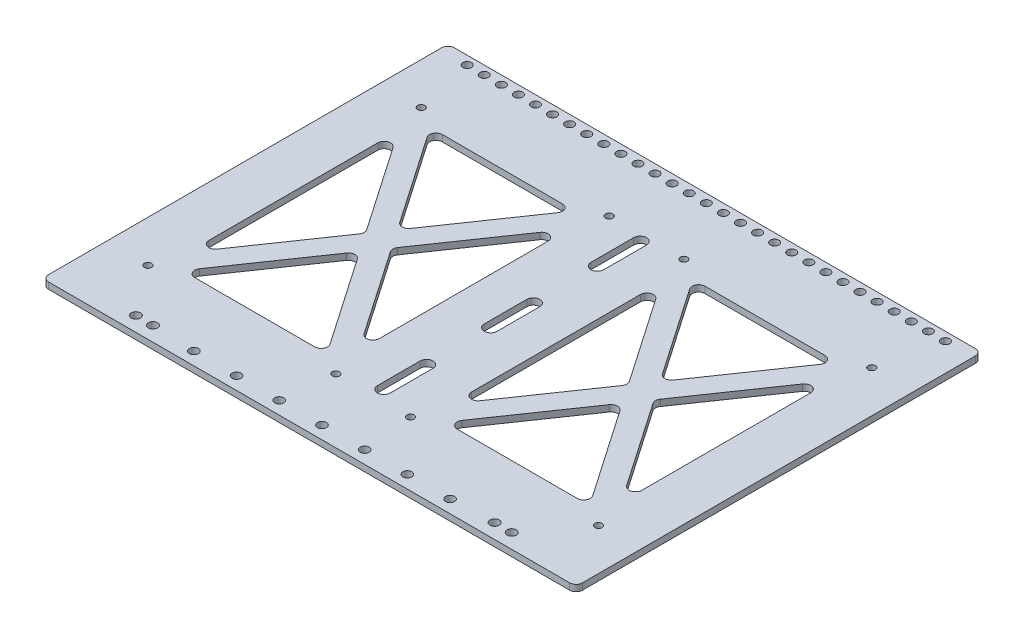
SolidWorks part; units mm, degrees
material "Thornel Mat VMA"
ref_plane "前视基准面" through (0, 0, 0) normal (0, 0, 1) x (1, 0, 0)
ref_plane "上视基准面" through (0, 0, 0) normal (0, 1, 0) x (1, 0, 0)
ref_plane "右视基准面" through (0, 0, 0) normal (1, 0, 0) x (0, 0, -1)
other "Configuration Table"
sketch "草图1" plane through (0, 0, 0) normal (0, 1, 0) x (1, 0, 0)
  line L1 (-125, -95) -> (125, -95)
  line L2 (-125, -95) -> (-125, 95)
  line L3 (-125, 95) -> (125, 95)
  line L4 (125, -95) -> (125, 95)
  line L5 (-125, -95) -> (125, 95) construction
  line L6 (-125, 95) -> (125, -95) construction
  point P0 (0, 0)
  dimension "D1" = 250
  dimension "D2" = 190
extrude "凸台-拉伸1" add sketch "草图1" along normal blind 3 contours L2 L1 L4 L3
sketch "草图2" plane through (0, 0, 0) normal (0, -1, 0) x (1, 0, 0)
  arc A4 (56, -93) -> (56, -89) centre (56, -91) ccw
  arc A5 (56, -89) -> (56, -93) centre (56, -91) ccw
  arc A8 (-112, -93) -> (-112, -89) centre (-112, -91) ccw
  arc A9 (-112, -89) -> (-112, -93) centre (-112, -91) ccw
  arc A12 (-104, -93) -> (-104, -89) centre (-104, -91) ccw
  arc A13 (-104, -89) -> (-104, -93) centre (-104, -91) ccw
  arc A16 (-96, -93) -> (-96, -89) centre (-96, -91) ccw
  arc A17 (-96, -89) -> (-96, -93) centre (-96, -91) ccw
  arc A20 (-88, -93) -> (-88, -89) centre (-88, -91) ccw
  arc A21 (-88, -89) -> (-88, -93) centre (-88, -91) ccw
  arc A24 (-48, -93) -> (-48, -89) centre (-48, -91) ccw
  arc A25 (-48, -89) -> (-48, -93) centre (-48, -91) ccw
  arc A28 (-80, -93) -> (-80, -89) centre (-80, -91) ccw
  arc A29 (-80, -89) -> (-80, -93) centre (-80, -91) ccw
  arc A32 (-72, -93) -> (-72, -89) centre (-72, -91) ccw
  arc A33 (-72, -89) -> (-72, -93) centre (-72, -91) ccw
  arc A36 (-64, -93) -> (-64, -89) centre (-64, -91) ccw
  arc A37 (-64, -89) -> (-64, -93) centre (-64, -91) ccw
  arc A40 (-56, -93) -> (-56, -89) centre (-56, -91) ccw
  arc A41 (-56, -89) -> (-56, -93) centre (-56, -91) ccw
  arc A44 (64, -93) -> (64, -89) centre (64, -91) ccw
  arc A45 (64, -89) -> (64, -93) centre (64, -91) ccw
  arc A48 (72, -93) -> (72, -89) centre (72, -91) ccw
  arc A49 (72, -89) -> (72, -93) centre (72, -91) ccw
  arc A52 (80, -93) -> (80, -89) centre (80, -91) ccw
  arc A53 (80, -89) -> (80, -93) centre (80, -91) ccw
  arc A56 (88, -93) -> (88, -89) centre (88, -91) ccw
  arc A57 (88, -89) -> (88, -93) centre (88, -91) ccw
  arc A60 (96, -93) -> (96, -89) centre (96, -91) ccw
  arc A61 (96, -89) -> (96, -93) centre (96, -91) ccw
  arc A64 (104, -93) -> (104, -89) centre (104, -91) ccw
  arc A65 (104, -89) -> (104, -93) centre (104, -91) ccw
  arc A68 (112, -93) -> (112, -89) centre (112, -91) ccw
  arc A69 (112, -89) -> (112, -93) centre (112, -91) ccw
  arc A72 (32, -93) -> (32, -89) centre (32, -91) ccw
  arc A73 (32, -89) -> (32, -93) centre (32, -91) ccw
  arc A76 (24, -93) -> (24, -89) centre (24, -91) ccw
  arc A77 (24, -89) -> (24, -93) centre (24, -91) ccw
  arc A80 (16, -93) -> (16, -89) centre (16, -91) ccw
  arc A81 (16, -89) -> (16, -93) centre (16, -91) ccw
  arc A84 (8, -93) -> (8, -89) centre (8, -91) ccw
  arc A85 (8, -89) -> (8, -93) centre (8, -91) ccw
  arc A88 (0, -93) -> (0, -89) centre (0, -91) ccw
  arc A89 (0, -89) -> (0, -93) centre (0, -91) ccw
  arc A92 (-8, -93) -> (-8, -89) centre (-8, -91) ccw
  arc A93 (-8, -89) -> (-8, -93) centre (-8, -91) ccw
  arc A96 (-16, -93) -> (-16, -89) centre (-16, -91) ccw
  arc A97 (-16, -89) -> (-16, -93) centre (-16, -91) ccw
  arc A100 (-24, -93) -> (-24, -89) centre (-24, -91) ccw
  arc A101 (-24, -89) -> (-24, -93) centre (-24, -91) ccw
  arc A104 (-32, -93) -> (-32, -89) centre (-32, -91) ccw
  arc A105 (-32, -89) -> (-32, -93) centre (-32, -91) ccw
  arc A108 (-40, -93) -> (-40, -89) centre (-40, -91) ccw
  arc A109 (-40, -89) -> (-40, -93) centre (-40, -91) ccw
  arc A112 (40, -93) -> (40, -89) centre (40, -91) ccw
  arc A113 (40, -89) -> (40, -93) centre (40, -91) ccw
  arc A116 (48, -93) -> (48, -89) centre (48, -91) ccw
  arc A117 (48, -89) -> (48, -93) centre (48, -91) ccw
extrude "切除-拉伸1" cut sketch "草图2" against normal through all both
sketch "草图3" plane through (0, 3, 0) normal (0, 1, 0) x (1, 0, 0)
  circle A2 centre (80, -88.1351) radius 2.15
  circle A3 centre (88, -88.1351) radius 2.15
  circle A6 centre (-80, -88.1351) radius 2.15
  circle A7 centre (-88, -88.1351) radius 2.15
  arc A16 (105.5, -66.7) -> (105.5, -63.3) centre (105.5, -65) ccw
  arc A17 (105.5, -63.3) -> (105.5, -66.7) centre (105.5, -65) ccw
  arc A18 (17.5, -63.3) -> (17.5, -66.7) centre (17.5, -65) ccw
  arc A19 (-17.5, -63.3) -> (-17.5, -66.7) centre (-17.5, -65) ccw
  arc A20 (-105.5, -66.7) -> (-105.5, -63.3) centre (-105.5, -65) ccw
  arc A21 (-105.5, -63.3) -> (-105.5, -66.7) centre (-105.5, -65) ccw
  arc A22 (17.5, -66.7) -> (17.5, -63.3) centre (17.5, -65) ccw
  arc A23 (-17.5, -66.7) -> (-17.5, -63.3) centre (-17.5, -65) ccw
  arc A32 (105.5, 61.3) -> (105.5, 64.7) centre (105.5, 63) ccw
  arc A33 (105.5, 64.7) -> (105.5, 61.3) centre (105.5, 63) ccw
  arc A34 (17.5, 64.7) -> (17.5, 61.3) centre (17.5, 63) ccw
  arc A35 (17.5, 61.3) -> (17.5, 64.7) centre (17.5, 63) ccw
  arc A36 (-17.5, 61.3) -> (-17.5, 64.7) centre (-17.5, 63) ccw
  arc A37 (-17.5, 64.7) -> (-17.5, 61.3) centre (-17.5, 63) ccw
  arc A38 (-105.5, 64.7) -> (-105.5, 61.3) centre (-105.5, 63) ccw
  arc A39 (-105.5, 61.3) -> (-105.5, 64.7) centre (-105.5, 63) ccw
extrude "切除-拉伸2" cut sketch "草图3" against normal through all
sketch "草图4" plane through (0, 3, 0) normal (0, 1, 0) x (1, 0, 0)
  line L0 (0, 0) -> (125, 0) construction
  line L1 (125, -95) -> (125, 95) construction
  line L2 (0, 0) -> (0, -95) construction
  line L3 (-125, -95) -> (125, -95) construction
  circle A0 centre (0, -89) radius 2.1
  circle A1 centre (20, -89) radius 2.1
  circle A2 centre (40, -89) radius 2.1
  circle A3 centre (60, -89) radius 2.1
  circle A4 centre (-60, -89) radius 2.1
  circle A5 centre (-40, -89) radius 2.1
  circle A6 centre (-20, -89) radius 2.1
  dimension "D1" = 4.2
  dimension "D2" = 6
  dimension "D3" = 4
extrude "切除-拉伸3" cut sketch "草图4" against normal through all
sketch "草图5" plane through (0, 3, 0) normal (0, 1, 0) x (1, 0, 0)
  line L0 (-105.5, 63) -> (-17.5, -65) construction
  line L1 (-17.5, -65) -> (17.5, -65) construction
  line L2 (17.5, -65) -> (105.5, 63) construction
  line L3 (0, 0) -> (0, -65) construction
  line L4 (-21.625, -59) -> (-101.375, -59)
  line L5 (-21.625, -59) -> (-21.625, 57)
  line L6 (-21.625, 57) -> (-101.375, 57)
  line L7 (-101.375, -59) -> (-101.375, 57)
  line L8 (-21.625, -59) -> (-101.375, 57) construction
  line L9 (-21.625, 57) -> (-101.375, -59) construction
  line L10 (-25.7452, 59.8326) -> (-105.4952, -56.1674)
  line L11 (-109.6202, 60.1674) -> (-21.6202, -67.8326)
  line L12 (-17.5048, 54.1674) -> (-97.2548, -61.8326)
  line L13 (-101.3798, 65.8326) -> (-13.3798, -62.1674)
  line L14 (21.625, 57) -> (101.375, -59) construction
  line L15 (21.625, -59) -> (101.375, 57) construction
  line L16 (105.5, 63) -> (17.5, -65) construction
  line L17 (101.3798, 65.8326) -> (13.3798, -62.1674)
  line L18 (17.5048, 54.1674) -> (97.2548, -61.8326)
  line L19 (109.6202, 60.1674) -> (21.6202, -67.8326)
  line L20 (25.7452, 59.8326) -> (105.4952, -56.1674)
  line L21 (101.375, -59) -> (101.375, 57)
  line L22 (21.625, 57) -> (101.375, 57)
  line L23 (21.625, -59) -> (21.625, 57)
  line L24 (21.625, -59) -> (101.375, -59)
  point P4 (-61.5, -1)
  point P36 (61.5, -1)
  dimension "D1" = 116
  dimension "D2" = 5
  dimension "D3" = 5
extrude "切除-拉伸4" cut sketch "草图5" against normal through all contours L6 L13 L10 | L11 L7 L10 | L11 L12 L4 | L12 L13 L5 | L23 L17 L18 | L22 L20 L17 | L20 L21 L19 | L19 L24 L18
fillet "圆角1" radius 3 28 edges at (21.625, 1.5, -48.1743) (55.4323, 1.5, 1) (21.625, 1.5, 50.1743) (-21.625, 1.5, 50.1743) (-55.4323, 1.5, 1) (-21.625, 1.5, -48.1743) (-27.6927, 1.5, 59) (-95.3073, 1.5, 59) (95.3073, 1.5, 59) (27.6927, 1.5, 59) (61.5, 1.5, 9.8257) (-125, 1.5, -95) (-125, 1.5, 95) (125, 1.5, 95) (125, 1.5, -95) (-61.5, 1.5, -7.8257) (-95.3073, 1.5, -57) (-27.6927, 1.5, -57) (101.375, 1.5, -48.1743) (101.375, 1.5, 50.1743) (67.5677, 1.5, 1) (95.3073, 1.5, -57) (61.5, 1.5, -7.8257) (27.6927, 1.5, -57) (-67.5677, 1.5, 1) (-101.375, 1.5, 50.1743) (-101.375, 1.5, -48.1743) (-61.5, 1.5, 9.8257)
sketch "草图6" plane through (0, 3, 0) normal (0, 1, 0) x (1, 0, 0)
  line L0 (0, -10) -> (0, 10) construction
  line L1 (-3, -10) -> (-3, 10)
  line L2 (3, -10) -> (3, 10)
  line L3 (3, 40) -> (3, 60)
  line L4 (-3, 40) -> (-3, 60)
  line L5 (0, 40) -> (0, 60) construction
  line L6 (3, -60) -> (3, -40)
  line L7 (-3, -60) -> (-3, -40)
  line L8 (0, -60) -> (0, -40) construction
  arc A0 (-3, -10) -> (3, -10) centre (0, -10) ccw
  arc A1 (3, 10) -> (-3, 10) centre (0, 10) ccw
  arc A2 (-3, 40) -> (3, 40) centre (0, 40) ccw
  arc A3 (3, 60) -> (-3, 60) centre (0, 60) ccw
  arc A4 (-3, -60) -> (3, -60) centre (0, -60) ccw
  arc A5 (3, -40) -> (-3, -40) centre (0, -40) ccw
  point P2 (0, 0)
  point P11 (0, 50)
  point P18 (0, -50)
  dimension "D1" = 3
  dimension "D2" = 20
  dimension "D5" = 50
  dimension "D3" = 2
  dimension "D4" = 2
extrude "切除-拉伸5" cut sketch "草图6" against normal through all
